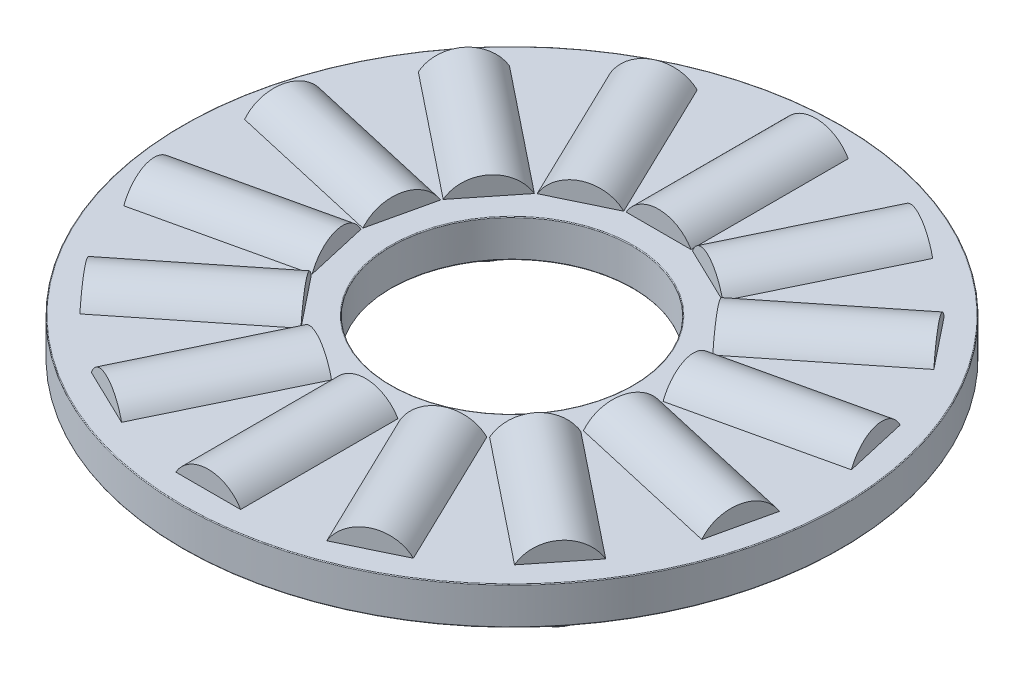
SolidWorks part; units mm, degrees
material "Plain Carbon Steel"
ref_plane "Front Plane" through (0, 0, 0) normal (0, 0, 1) x (1, 0, 0)
ref_plane "Top Plane" through (0, 0, 0) normal (0, 1, 0) x (1, 0, 0)
ref_plane "Right Plane" through (0, 0, 0) normal (1, 0, 0) x (0, 0, -1)
sketch "Sketch1" plane through (0, 0, 0) normal (1, 0, 0) x (0, 0, -1)
  line L0 (-8.7312, 0) -> (8.7312, 0) construction
  line L1 (0, -0.9922) -> (0, 0.9922) construction
  line L2 (-8.7312, 0.4961) -> (-3.2004, 0.4961)
  line L3 (-8.7312, 0.4961) -> (-8.7312, -0.4961)
  line L4 (-8.7312, -0.4961) -> (-3.2004, -0.4961)
  line L5 (-3.2004, 0.4961) -> (-3.2004, -0.4961)
  line L7 (-5.9658, 0.9922) -> (-5.9658, 0.4961) construction
  line L8 (-8.0494, 0.9922) -> (-3.8822, 0.9922) construction
  line L9 (-8.0494, 0.9922) -> (-8.0494, -0.9922) construction
  line L10 (-8.0494, -0.9922) -> (-3.8822, -0.9922) construction
  line L11 (-3.8822, 0.9922) -> (-3.8822, -0.9922) construction
  point P16 (-8.0494, 0)
  dimension "OD" = 17.4625
  dimension "Shaft Dia" = 6.4008
  dimension "Th" = 1.9844
  dimension "D2" = 0.9922
  dimension "D1" = 4.1672
  dimension "D3" = 5.5308
revolve "Revolve1" add sketch "Sketch1" angle 360 about L1
sketch "Sketch3" plane through (0, 0, 0) normal (1, 0, 0) x (0, 0, -1)
  line L0 (-8.0494, 0.9922) -> (-8.0494, -0.9922) construction
  line L1 (-8.0494, 0) -> (-3.8822, 0)
  line L2 (-8.0494, 0) -> (-8.0494, 0.9922)
  line L3 (-8.0494, 0.9922) -> (-3.8822, 0.9922)
  line L4 (-3.8822, 0) -> (-3.8822, 0.9922)
revolve "Cut-Revolve1" cut sketch "Sketch3" angle 360 about L1
sketch "Sketch2" plane through (0, 0, 0) normal (1, 0, 0) x (0, 0, -1)
  line L1 (-8.0494, 0) -> (-3.8822, 0)
  line L2 (-8.0494, 0) -> (-8.0494, 0.9922)
  line L3 (-8.0494, 0.9922) -> (-3.8822, 0.9922)
  line L4 (-3.8822, 0) -> (-3.8822, 0.9922)
revolve "Revolve2" add sketch "Sketch2" angle 360 about L1
ref_axis "Axis1" through (0, 0.9922, 0) along (0, -1, 0)
pattern_circular "CirPattern1" count 14 every 25.714 about axis through (0, 0.9922, 0) along (0, -1, 0) of bodies 187 411
pattern_circular "CirPattern2" count 14 every 25.714 about axis through (0, 0, 0) along (0, 1, 0) of "Cut-Revolve1"
sketch "Sketch4" plane through (0, 0, 0) normal (1, 0, 0) x (0, 0, -1)
  line L0 (-8.7312, 0.4961) -> (-8.7312, -0.4961) construction
  line L1 (-11.9062, 9.1091) -> (-6.35, 9.1091)
  line L2 (-11.9062, 9.1091) -> (-11.9062, 9.9219)
  line L3 (-11.9062, 9.9219) -> (-6.35, 9.9219)
  line L4 (-6.35, 9.1091) -> (-6.35, 9.9219)
  line L5 (-11.9062, -9.9219) -> (-3.2004, -9.9219)
  line L6 (-11.9062, -9.9219) -> (-11.9062, -9.1091)
  line L7 (-11.9062, -9.1091) -> (-3.2004, -9.1091)
  line L8 (-3.2004, -9.9219) -> (-3.2004, -9.1091)
  line L10 (-3.2004, 0.4961) -> (-3.2004, -0.4961) construction
  line L11 (0, 0) -> (-8.7312, 0) construction
  line L12 (-8.7312, 0) -> (8.7312, 0) construction
  line L13 (0, -0.9922) -> (0, 0.9922) construction
  dimension "Ht" = 19.8438
  dimension "Washer Th" = 0.8128
  dimension "Washer ID" = 12.7
  dimension "Washer OD" = 23.8125
fillet "Fillet2" radius 0.0198 4 edges at (0, -0.4961, -3.2004) (0, 0.4961, -3.2004) (0, -0.4961, -8.7312) (0, 0.4961, -8.7312)
equation "\"D2@Sketch1\"= \"Th@Sketch1\" * .5"
equation "\"Rollers@CirPattern1\"= \"OD@Sketch1\" * 20"
equation "\"Angle@CirPattern1\" = 360/\"Rollers@CirPattern1\""
equation "\"D1@CirPattern2\" = \"Rollers@CirPattern1\""
equation "\"D2@CirPattern2\" = \"Angle@CirPattern1\""
equation "\"Ht@Sketch4\" = \"Th@Sketch1\"*10"
